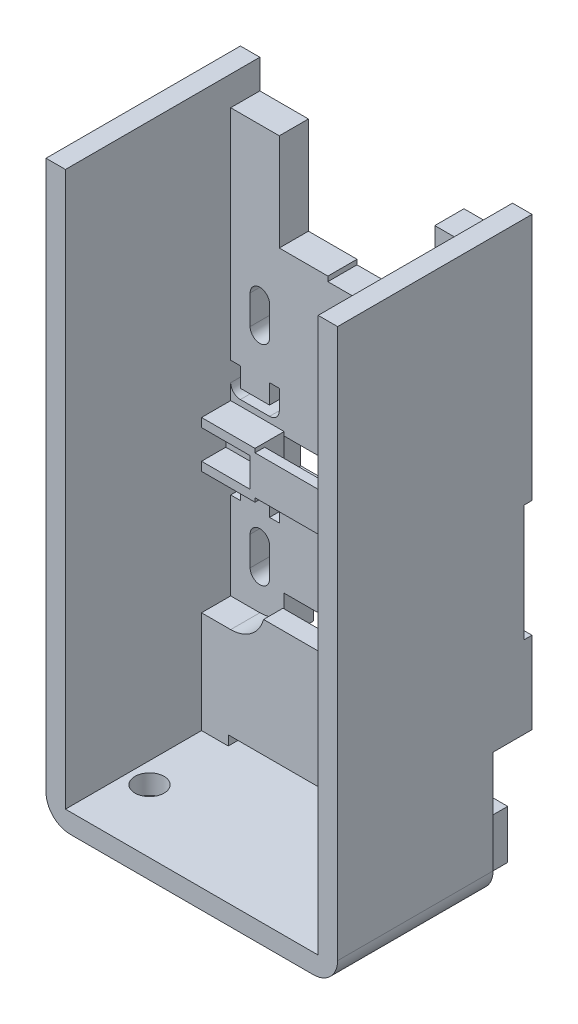
SolidWorks part; units mm, degrees
material "PA Type 6"
ref_plane "Front Plane" through (0, 0, 0) normal (0, 0, 1) x (1, 0, 0)
ref_plane "Top Plane" through (0, 0, 0) normal (0, 1, 0) x (1, 0, 0)
ref_plane "Right Plane" through (0, 0, 0) normal (1, 0, 0) x (0, 0, -1)
sketch "Sketch1" plane through (0, 0, 0) normal (0, 0, 1) x (1, 0, 0)
  line L0 (15, -29.5) -> (-15, 29.5) construction
  line L1 (-15, 29.5) -> (15, 29.5)
  line L2 (-15, 29.5) -> (-15, -27)
  line L3 (-12.5, -29.5) -> (12.5, -29.5)
  line L4 (15, 29.5) -> (15, -27)
  arc A0 (-15, -27) -> (-12.5, -29.5) centre (-12.5, -27) ccw
  arc A1 (12.5, -29.5) -> (15, -27) centre (12.5, -27) ccw
  dimension "D3" = 2.5
  dimension "D1" = 30
  dimension "D2" = 59
extrude "Boss-Extrude1" add sketch "Sketch1" along normal blind 20
sketch "Sketch2" plane through (0, 0, 0) normal (0, 0, -1) x (-1, 0, 0)
  line L0 (-13, 29.5) -> (-13, 26.5)
  line L1 (-15, 29.5) -> (15, 29.5) construction
  line L2 (-13, 26.5) -> (-8, 26.5)
  line L3 (-8, 26.5) -> (-8, 16.5)
  line L4 (-8, 16.5) -> (-3, 16.5)
  line L5 (-3, 16.5) -> (-3, 16)
  line L6 (-3, 16) -> (3, 16)
  line L7 (3, 16) -> (3, 16.5)
  line L8 (3, 16.5) -> (8, 16.5)
  line L9 (8, 16.5) -> (8, 26.5)
  line L10 (8, 26.5) -> (13, 26.5)
  line L11 (13, 26.5) -> (13, 29.5)
  line L12 (13, 29.5) -> (-13, 29.5)
  line L13 (0, 16) -> (0, 0) construction
  dimension "D1" = 26
  dimension "D2" = 3
  dimension "D3" = 6
  dimension "D4" = 16
  dimension "D5" = 13
  dimension "D6" = 0.5
extrude "Cut-Extrude1" cut sketch "Sketch2" against normal through all
sketch "Sketch3" plane through (0, 0, 0) normal (0, 0, -1) x (-1, 0, 0)
  line L0 (-10, 11) -> (-10, 8) construction
  line L1 (-9, 11) -> (-9, 8)
  line L2 (-11, 11) -> (-11, 8)
  line L3 (10, 8) -> (10, 11) construction
  line L4 (9, 8) -> (9, 11)
  line L5 (11, 8) -> (11, 11)
  line L6 (10, -13.5) -> (10, -10.5) construction
  line L7 (9, -13.5) -> (9, -10.5)
  line L8 (11, -13.5) -> (11, -10.5)
  line L9 (-10, -10.5) -> (-10, -13.5) construction
  line L10 (-9, -10.5) -> (-9, -13.5)
  line L11 (-11, -10.5) -> (-11, -13.5)
  line L12 (-10, -10.5) -> (-10, 8) construction
  line L13 (-10, 9.5) -> (10, 9.5) construction
  line L14 (10, 8) -> (10, -10.5) construction
  line L15 (-10, -12) -> (10, -12) construction
  line L16 (0, -12) -> (0, 0) construction
  line L17 (-8, 16.5) -> (-3, 16.5) construction
  arc A0 (-9, 11) -> (-11, 11) centre (-10, 11) ccw
  arc A1 (-11, 8) -> (-9, 8) centre (-10, 8) ccw
  arc A2 (9, 8) -> (11, 8) centre (10, 8) ccw
  arc A3 (11, 11) -> (9, 11) centre (10, 11) ccw
  arc A4 (9, -13.5) -> (11, -13.5) centre (10, -13.5) ccw
  arc A5 (11, -10.5) -> (9, -10.5) centre (10, -10.5) ccw
  arc A6 (-9, -10.5) -> (-11, -10.5) centre (-10, -10.5) ccw
  arc A7 (-11, -13.5) -> (-9, -13.5) centre (-10, -13.5) ccw
  point P2 (-10, 9.5)
  point P7 (10, 9.5)
  point P16 (10, -12)
  point P21 (-10, -12)
  dimension "D1" = 2
  dimension "D2" = 3
  dimension "D3" = 5.5
  dimension "D4" = 22
  dimension "D5" = 21.5
extrude "Cut-Extrude2" cut sketch "Sketch3" against normal through all
sketch "Sketch4" plane through (0, 0, 20) normal (0, 0, 1) x (1, 0, 0)
  line L0 (15, 29.5) -> (13, 29.5) construction
  line L1 (-13, -27.5) -> (13, -27.5)
  line L2 (-13, -27.5) -> (-13, 29.5)
  line L3 (-13, 29.5) -> (13, 29.5)
  line L4 (13, -27.5) -> (13, 29.5)
  line L5 (0, 29.5) -> (0, 0) construction
  line L6 (-12.5, -29.5) -> (12.5, -29.5) construction
  dimension "D1" = 26
  dimension "D2" = 2
extrude "Cut-Extrude3" cut sketch "Sketch4" against normal blind 14
sketch "Sketch5" plane through (0, 0, 0) normal (0, 0, -1) x (-1, 0, 0)
  line L0 (-15, 4) -> (-12, 4)
  line L1 (-15, -27) -> (-15, 29.5) construction
  line L2 (-12, 4) -> (-12, 2)
  line L3 (-12, 2) -> (-9, 2)
  line L4 (-9, 2) -> (-9, 4)
  line L5 (-9, 4) -> (9, 4)
  line L6 (9, 4) -> (9, 2)
  line L7 (9, 2) -> (12, 2)
  line L8 (12, 2) -> (12, 4)
  line L9 (12, 4) -> (15, 4)
  line L10 (15, 29.5) -> (15, -27) construction
  line L11 (15, 4) -> (15, -8)
  line L12 (15, -8) -> (12, -8)
  line L13 (12, -8) -> (12, -6)
  line L14 (12, -6) -> (9, -6)
  line L15 (9, -6) -> (9, -8)
  line L16 (9, -8) -> (5.5, -8)
  line L17 (5.5, -8) -> (5.5, -14)
  line L18 (5.5, -14) -> (-5.5, -14)
  line L19 (-5.5, -14) -> (-5.5, -8)
  line L20 (-5.5, -8) -> (-9, -8)
  line L21 (-9, -8) -> (-9, -6)
  line L22 (-9, -6) -> (-12, -6)
  line L23 (-12, -6) -> (-12, -8)
  line L24 (-12, -8) -> (-15, -8)
  line L25 (-15, -8) -> (-15, 4)
  arc A0 (-11, 8) -> (-9, 8) centre (-10, 8) ccw construction
  dimension "D1" = 2
  dimension "D2" = 3
  dimension "D3" = 3
  dimension "D4" = 8
  dimension "D5" = 6
  dimension "D6" = 11
  dimension "D7" = 6
extrude "Cut-Extrude4" cut sketch "Sketch5" against normal blind 0.8
sketch "Sketch6" plane through (0, 0, 0.8) normal (0, 0, -1) x (-1, 0, 0)
  line L0 (-12, 4) -> (-12, 2)
  line L1 (-12, 2) -> (-9, 2)
  line L2 (-9, 2) -> (-9, 4)
  line L3 (-9, 4) -> (-8, 4)
  line L4 (9, 4) -> (-9, 4) construction
  line L5 (-8, 4) -> (-8, 2)
  line L6 (-9, 1) -> (-12, 1)
  line L7 (-13, 2) -> (-13, 4)
  line L8 (-12, 4) -> (-15, 4) construction
  line L9 (-13, 4) -> (-12, 4)
  line L10 (0, 0) -> (0, 4) construction
  line L11 (-10.5, 2) -> (-10.5, -6) construction
  line L12 (-12, -6) -> (-9, -6) construction
  line L13 (-10.5, -2) -> (0, -2) construction
  line L14 (0, -2) -> (0, 0) construction
  line L15 (13, 4) -> (12, 4)
  line L16 (13, 2) -> (13, 4)
  line L17 (9, 1) -> (12, 1)
  line L18 (8, 4) -> (8, 2)
  line L19 (9, 4) -> (8, 4)
  line L20 (9, 2) -> (9, 4)
  line L21 (12, 2) -> (9, 2)
  line L22 (12, 4) -> (12, 2)
  line L23 (12, -8) -> (12, -6)
  line L24 (12, -6) -> (9, -6)
  line L25 (9, -6) -> (9, -8)
  line L26 (9, -8) -> (8, -8)
  line L27 (8, -8) -> (8, -6)
  line L28 (9, -5) -> (12, -5)
  line L29 (13, -6) -> (13, -8)
  line L30 (13, -8) -> (12, -8)
  line L31 (-13, -8) -> (-12, -8)
  line L32 (-13, -6) -> (-13, -8)
  line L33 (-9, -5) -> (-12, -5)
  line L34 (-8, -8) -> (-8, -6)
  line L35 (-9, -8) -> (-8, -8)
  line L36 (-9, -6) -> (-9, -8)
  line L37 (-12, -6) -> (-9, -6)
  line L38 (-12, -8) -> (-12, -6)
  arc A0 (-8, 2) -> (-9, 1) centre (-9, 2) cw
  arc A1 (-12, 1) -> (-13, 2) centre (-12, 2) cw
  arc A2 (12, 1) -> (13, 2) centre (12, 2) ccw
  arc A3 (8, 2) -> (9, 1) centre (9, 2) ccw
  arc A4 (8, -6) -> (9, -5) centre (9, -6) cw
  arc A5 (12, -5) -> (13, -6) centre (12, -6) cw
  arc A6 (-12, -5) -> (-13, -6) centre (-12, -6) ccw
  arc A7 (-8, -6) -> (-9, -5) centre (-9, -6) ccw
  dimension "D1" = 1
extrude "Cut-Extrude5" cut sketch "Sketch6" against normal through all
sketch "Sketch7" plane through (0, 0, 0) normal (0, 0, -1) x (-1, 0, 0)
  line L0 (-7.5, -14) -> (7.5, -14)
  line L1 (7.5, -14) -> (7.5, -18)
  line L2 (7.5, -18) -> (10.8289, -19.9219)
  line L3 (10.8289, -19.9219) -> (15, -16.4219)
  line L4 (15, -8) -> (15, -27) construction
  line L5 (15, -16.4219) -> (15, -27)
  line L6 (12.5, -29.5) -> (12.5, -24.5)
  line L7 (12.5, -24.5) -> (-12.5, -24.5)
  line L8 (0, -24.5) -> (0, -14) construction
  line L9 (-5.5, -14) -> (5.5, -14) construction
  line L10 (-12.5, -29.5) -> (-12.5, -24.5)
  line L11 (-15, -16.4219) -> (-15, -27)
  line L12 (-10.8289, -19.9219) -> (-15, -16.4219)
  line L13 (-7.5, -18) -> (-10.8289, -19.9219)
  line L14 (-7.5, -14) -> (-7.5, -18)
  arc A0 (15, -27) -> (12.5, -29.5) centre (12.5, -27) cw
  arc A1 (-15, -27) -> (-12.5, -29.5) centre (-12.5, -27) ccw
  dimension "D1" = 15
  dimension "D2" = 4
  dimension "D3" = 60
  dimension "D4" = 50
  dimension "D5" = 3.5
  dimension "D6" = 5
extrude "Cut-Extrude6" cut sketch "Sketch7" against normal blind 4
sketch "Sketch8" plane through (0, 0, 4) normal (0, 0, -1) x (-1, 0, 0)
  line L1 (-12.5, -24.5) -> (-7.5, -24.5)
  line L2 (-12.5, -24.5) -> (-12.5, -18)
  line L3 (-12.5, -18) -> (-7.5, -18)
  line L4 (-7.5, -24.5) -> (-7.5, -18)
  line L5 (7.5, -18) -> (12.5, -18)
  line L6 (7.5, -18) -> (7.5, -24.5)
  line L7 (7.5, -24.5) -> (12.5, -24.5)
  line L8 (12.5, -18) -> (12.5, -24.5)
extrude "Boss-Extrude2" add sketch "Sketch8" along normal blind 1
sketch "Sketch9" plane through (0, 0, 0) normal (0, 0, -1) x (-1, 0, 0)
  line L0 (0, -27.5) -> (0, -29.5) construction
  line L1 (-10.25, -26.5) -> (10.25, -26.5)
  line L2 (-10.25, -26.5) -> (-10.25, -27.5)
  line L3 (-10.25, -27.5) -> (10.25, -27.5)
  line L4 (10.25, -26.5) -> (10.25, -27.5)
  line L5 (12.5, -29.5) -> (-12.5, -29.5) construction
  dimension "D1" = 20.5
  dimension "D2" = 1
  dimension "D3" = 2
extrude "Cut-Extrude7" cut sketch "Sketch9" against normal through all
sketch "Sketch10" plane through (0, 0, 0) normal (0, 0, -1) x (-1, 0, 0)
  line L0 (-12.5, -24.5) -> (12.5, -24.5) construction
  line L1 (-5.75, -24.5) -> (5.75, -24.5)
  line L2 (-5.75, -24.5) -> (-5.75, -26.5)
  line L3 (-5.75, -26.5) -> (5.75, -26.5)
  line L4 (5.75, -24.5) -> (5.75, -26.5)
  line L5 (10.25, -26.5) -> (-10.25, -26.5) construction
  line L6 (0, -26.5) -> (0, -29.5) construction
  line L7 (12.5, -29.5) -> (-12.5, -29.5) construction
  dimension "D1" = 11.5
extrude "Cut-Extrude8" cut sketch "Sketch10" against normal blind 1
sketch "Sketch11" plane through (0, 0, 6) normal (0, 0, 1) x (1, 0, 0)
  line L0 (-13, 26.5) -> (-13, 0.4)
  line L1 (-13, 2) -> (-13, -6) construction
  line L2 (-13, 0.4) -> (-7.5, 0.4)
  line L3 (-7.5, 0.4) -> (-7.5, 0)
  line L4 (-7.5, 0) -> (7.5, 0)
  line L5 (7.5, 0) -> (7.5, 0.4)
  line L6 (7.5, 0.4) -> (13, 0.4)
  line L7 (13, 29.5) -> (13, -27.5) construction
  line L8 (13, 0.4) -> (13, 26.5)
  line L9 (13, 26.5) -> (-13, 26.5)
  line L10 (-9, 1) -> (-12, 1) construction
  line L11 (-10.5, 1) -> (-10.5, -5) construction
  line L12 (-12, -5) -> (-9, -5) construction
  line L13 (-10.5, -2) -> (0, -2) construction
  line L14 (7.5, -4.4) -> (13, -4.4)
  line L15 (7.5, -4) -> (7.5, -4.4)
  line L16 (-7.5, -4) -> (7.5, -4)
  line L17 (-7.5, -4.4) -> (-7.5, -4)
  line L18 (-13, -4.4) -> (-7.5, -4.4)
  line L19 (-13, -4.4) -> (-13, -17)
  line L21 (-13, -17) -> (-10, -17)
  line L22 (-6.6193, -14.4059) -> (6.6193, -14.4059)
  line L23 (0, -14.4059) -> (0, 0) construction
  line L24 (-6.6193, -14.4059) -> (-5.1419, -8.8925) construction
  line L25 (6.6193, -14.4059) -> (5.1419, -8.8925) construction
  line L26 (13, -17) -> (10, -17)
  line L27 (13, -4.4) -> (13, -17)
  arc A0 (-10, -17) -> (-6.6193, -14.4059) centre (-10, -13.5) ccw
  arc A1 (-11, -13.5) -> (-9, -13.5) centre (-10, -13.5) ccw construction
  arc A2 (10, -17) -> (6.6193, -14.4059) centre (10, -13.5) cw
  dimension "D5" = 2.5
  dimension "D1" = 0.6
  dimension "D2" = 0.4
  dimension "D3" = 15
  dimension "D4" = 75
extrude "Cut-Extrude9" cut sketch "Sketch11" against normal blind 3
sketch "Sketch12" plane through (0, 0, 0) normal (0, 1, 0) x (1, 0, 0)
  line L0 (7.5, -3) -> (7.5, -6) construction
  line L1 (-7.5, -3) -> (7.5, -3)
  line L2 (-7.5, -3) -> (-7.5, -5)
  line L3 (-7.5, -5) -> (7.5, -5)
  line L4 (7.5, -3) -> (7.5, -5)
  line L5 (-7.5, -6) -> (7.5, -6) construction
  dimension "D1" = 1
extrude "Cut-Extrude10" cut sketch "Sketch12" against normal up to next
sketch "Sketch13" plane through (0, 0, 0.8) normal (0, 0, -1) x (-1, 0, 0)
  line L0 (-9, 2) -> (9, -6) construction
  line L1 (-8, 0) -> (8, 0)
  line L2 (-8, 0) -> (-8, -4)
  line L3 (-8, -4) -> (8, -4)
  line L4 (8, 0) -> (8, -4)
  line L5 (0, -2) -> (0, -6) construction
  line L6 (-8, -4) -> (8, 0) construction
  line L7 (-12, 1) -> (-9, 1) construction
  dimension "D1" = 1
  dimension "D2" = 16
extrude "Cut-Extrude11" cut sketch "Sketch13" against normal blind 2.2
sketch "Sketch14" plane through (0, 0, 6) normal (0, 0, 1) x (1, 0, 0)
  line L0 (-13, -27.5) -> (-13, 29.5) construction
  line L1 (-13, -0.5) -> (-8, -0.5)
  line L2 (-13, -0.5) -> (-13, -3.5)
  line L3 (-13, -3.5) -> (-8, -3.5)
  line L4 (-8, -0.5) -> (-8, -3.5)
  line L5 (13, -4.4) -> (13, 0.4) construction
  line L6 (13, -0.5) -> (8, -0.5)
  line L7 (13, -0.5) -> (13, -3.5)
  line L8 (13, -3.5) -> (8, -3.5)
  line L9 (8, -0.5) -> (8, -3.5)
  line L10 (0, 0) -> (0, -4) construction
  line L11 (-7.5, 0) -> (7.5, 0) construction
  line L12 (7.5, -4) -> (-7.5, -4) construction
  line L13 (-8, -2) -> (0, -2) construction
  line L14 (0, -2) -> (8, -2) construction
  line L15 (7.5, -4) -> (-7.5, -4) construction
  dimension "D1" = 3
  dimension "D2" = 5
extrude "Cut-Extrude12" cut sketch "Sketch14" against normal blind 2.5
sketch "Sketch15" plane through (0, -29.5, 0) normal (0, -1, 0) x (1, 0, 0)
  line L0 (10.85, 13.5) -> (-10.85, 13.5) construction
  line L1 (0, 13.5) -> (0, 0) construction
  line L2 (-12.5, 0) -> (12.5, 0) construction
  line L3 (-12.5, 20) -> (12.5, 20) construction
  circle A0 centre (-10.85, 13.5) radius 1.5
  circle A1 centre (10.85, 13.5) radius 1.5
  dimension "D1" = 3
  dimension "D2" = 21.7
  dimension "D3" = 6.5
extrude "Cut-Extrude13" cut sketch "Sketch15" against normal up to next
